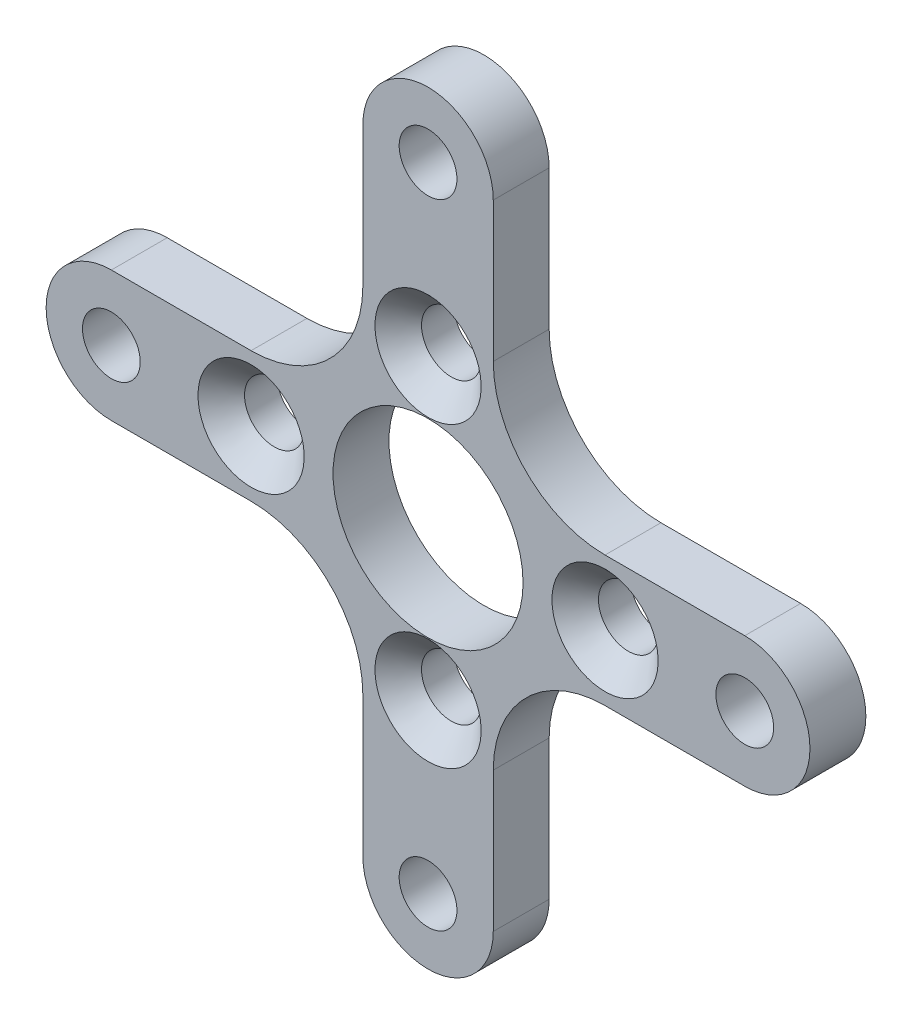
SolidWorks part; units mm, degrees
material "ASTM A36 Steel"
ref_plane "Front Plane" through (0, 0, 0) normal (1, 0, 0) x (0, 1, 0)
ref_plane "Top Plane" through (0, 0, 0) normal (0, 0, 1) x (0, 1, 0)
ref_plane "Right Plane" through (0, 0, 0) normal (0, 1, 0) x (-1, 0, 0)
sketch "Sketch1" plane through (0, 0, 0) normal (0, 0, 1) x (0, 1, 0)
  line L0 (0, 20.5) -> (0, -20.5) construction
  line L1 (-20.5, 0) -> (20.5, 0) construction
  line L2 (-8, 0) -> (8, 0) construction
  line L3 (0, 9.5) -> (0, -9.5) construction
  line L4 (-17, 0) -> (17, 0) construction
  line L5 (0, 17) -> (0, -17) construction
  line L6 (3.5, 17) -> (3.5, 9.5)
  line L7 (-3.5, 17) -> (-3.5, 9.5)
  line L8 (-17, 3.5) -> (-9.5, 3.5)
  line L9 (17, 3.5) -> (9.5, 3.5)
  line L10 (-17, -3.5) -> (-9.5, -3.5)
  line L11 (-3.5, -9.5) -> (-3.5, -17)
  line L12 (3.5, -17) -> (3.5, -9.5)
  line L13 (9.5, -3.5) -> (17, -3.5)
  circle A0 centre (0, 0) radius 5.1
  circle A1 centre (0, 9.5) radius 1.6
  circle A2 centre (8, 0) radius 1.6
  circle A3 centre (-8, 0) radius 1.6
  circle A4 centre (0, -9.5) radius 1.6
  circle A5 centre (0, 17) radius 1.55
  circle A6 centre (17, 0) radius 1.55
  circle A7 centre (-17, 0) radius 1.55
  circle A8 centre (0, -17) radius 1.55
  arc A9 (-3.5, 17) -> (3.5, 17) centre (0, 17) cw
  arc A10 (-17, -3.5) -> (-17, 3.5) centre (-17, 0) cw
  arc A11 (3.5, -17) -> (-3.5, -17) centre (0, -17) cw
  arc A12 (17, 3.5) -> (17, -3.5) centre (17, 0) cw
  arc A13 (3.5, -9.5) -> (9.5, -3.5) centre (9.5, -9.5) cw
  arc A14 (3.5, 9.5) -> (9.5, 3.5) centre (9.5, 9.5) ccw
  arc A15 (-3.5, -9.5) -> (-9.5, -3.5) centre (-9.5, -9.5) ccw
  arc A16 (-3.5, 9.5) -> (-9.5, 3.5) centre (-9.5, 9.5) cw
  point P18 (0, 0)
  point P19 (0, 0)
  point P21 (0, 0)
  point P23 (0, 0)
  dimension "D1" = 10.2
  dimension "D2" = 3.2
  dimension "D7" = 3.1
  dimension "D8" = 7
  dimension "D9" = 6
  dimension "D3" = 19
  dimension "D4" = 16
  dimension "D5" = 34
  dimension "D6" = 34
extrude "Boss-Extrude1" add sketch "Sketch1" along normal blind 3
chamfer "Chamfer1" distance 1.25 angle 45 4 edges at (11.1, 0, 3) (1.6, 8, 3) (-7.9, 0, 3) (1.6, -8, 3)
